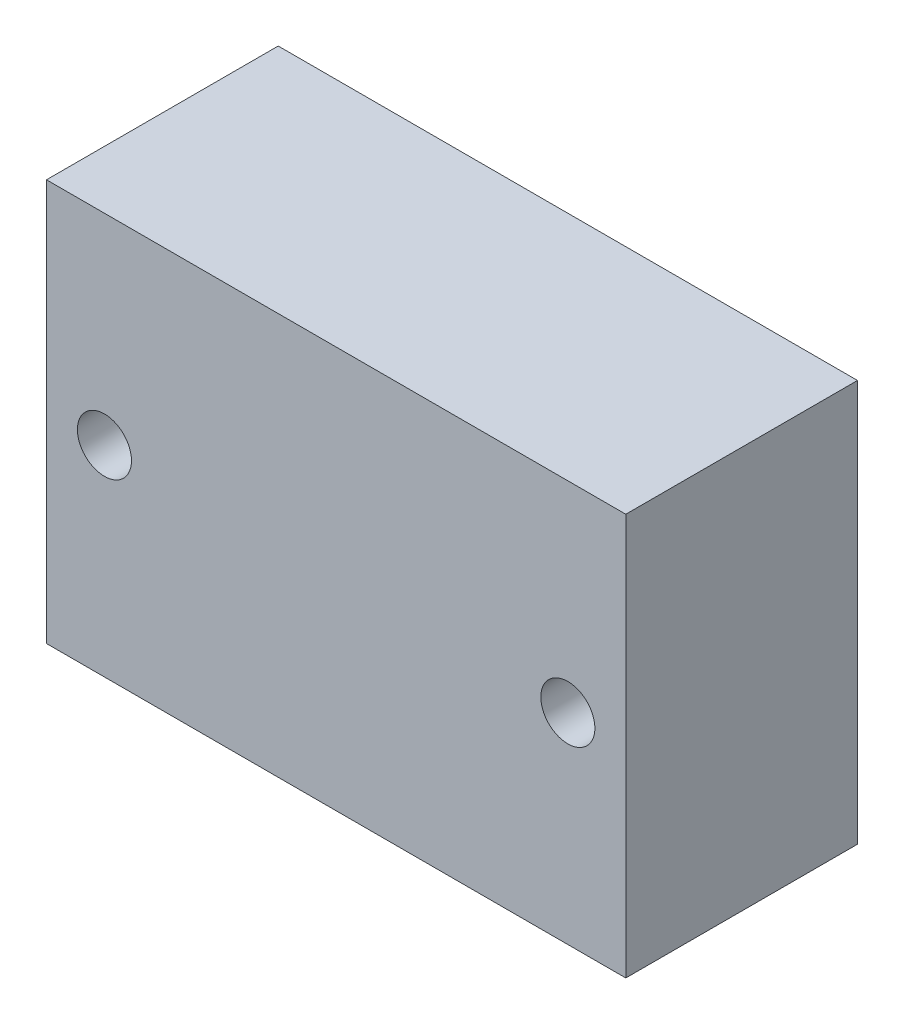
SolidWorks part; units mm, degrees
ref_plane "Front Plane" through (0, 0, 0) normal (0, 0, 1) x (1, 0, 0)
ref_plane "Top Plane" through (0, 0, 0) normal (0, 1, 0) x (1, 0, 0)
ref_plane "Right Plane" through (0, 0, 0) normal (1, 0, 0) x (0, 0, -1)
sketch "Sketch1" plane through (0, 0, 0) normal (0, 0, 1) x (1, 0, 0)
  line L0 (37.5, 0) -> (37.5, -52) construction
  line L1 (0, 0) -> (75, 0)
  line L2 (0, 0) -> (0, -52)
  line L3 (0, -52) -> (75, -52)
  line L4 (75, 0) -> (75, -52)
  circle A0 centre (7.5, -26) radius 3.5
  circle A1 centre (67.5, -26) radius 3.5
  dimension "D3" = 30
  dimension "D1" = 75
  dimension "D2" = 52
  dimension "D4" = 26
extrude "Boss-Extrude1" add sketch "Sketch1" along normal blind 30
